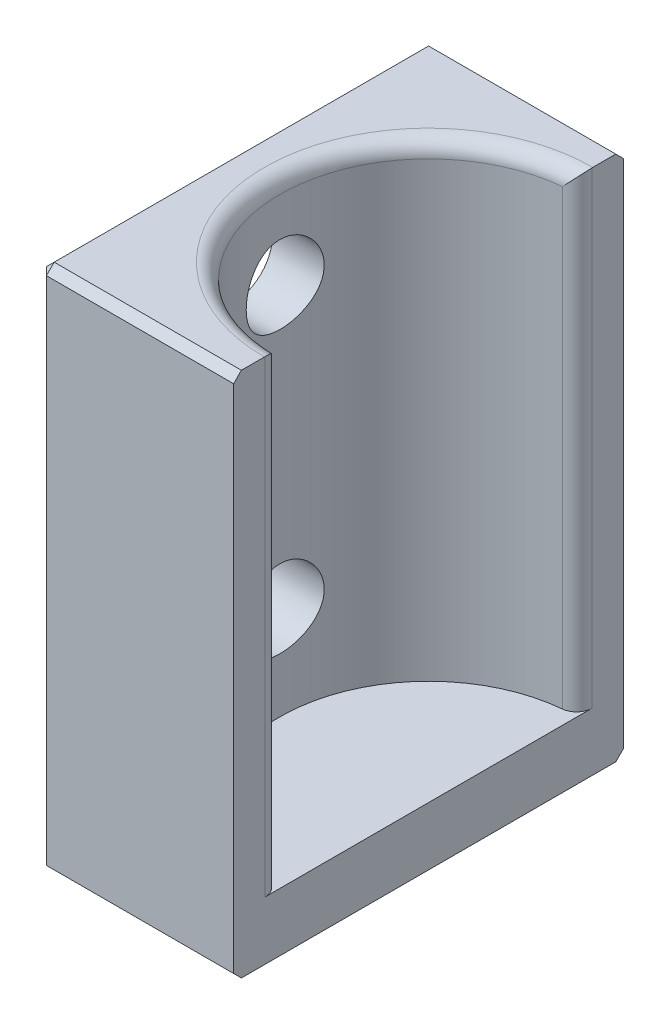
SolidWorks part; units mm, degrees
ref_plane "Front" through (0, 0, 0) normal (0, 0, 1) x (1, 0, 0)
ref_plane "Top" through (0, 0, 0) normal (0, 1, 0) x (1, 0, 0)
ref_plane "Right" through (0, 0, 0) normal (1, 0, 0) x (0, 0, -1)
sketch "Sketch1" plane through (0, 0, 0) normal (0, 1, 0) x (1, 0, 0)
  line L1 (-12.5, -12.5) -> (12.5, -12.5)
  line L2 (-12.5, -12.5) -> (-12.5, 12.5)
  line L3 (-12.5, 12.5) -> (12.5, 12.5)
  line L4 (12.5, -12.5) -> (12.5, 12.5)
  line L5 (-12.5, -12.5) -> (12.5, 12.5) construction
  line L6 (-12.5, 12.5) -> (12.5, -12.5) construction
  point P0 (0, 0)
  dimension "D1" = 25
extrude "Boss-Extrude1" add sketch "Sketch1" along normal blind 33.74
sketch "Sketch2" plane through (0, 33.74, 0) normal (0, 1, 0) x (1, 0, 0)
  line L0 (-12.5, 12.5) -> (12.5, -12.5) construction
  circle A0 centre (0, 0) radius 9.525
  dimension "D1" = 19.05
extrude "Cut-Extrude1" cut sketch "Sketch2" against normal blind 30
sketch "Sketch3" plane through (0, 33.74, 0) normal (0, 1, 0) x (1, 0, 0)
  line L0 (0, 12.5) -> (0, -12.5)
  line L1 (12.5, 12.5) -> (-12.5, 12.5) construction
  line L2 (-12.5, -12.5) -> (12.5, -12.5) construction
  line L3 (0, -12.5) -> (12.5, -12.5)
  line L4 (12.5, -12.5) -> (12.5, 12.5)
  line L5 (12.5, 12.5) -> (0, 12.5)
extrude "Cut-Extrude2" cut sketch "Sketch3" against normal through all
sketch "Sketch4" plane through (-12.5, 0, 0) normal (-1, 0, 0) x (0, 0, 1)
  line L0 (0, 33.74) -> (0, 3.74) construction
  line L1 (-12.5, 33.74) -> (12.5, 33.74) construction
  line L2 (-12.5, 18.74) -> (12.5, 18.74) construction
  line L3 (-12.5, 33.74) -> (-12.5, 0) construction
  line L4 (12.5, 33.74) -> (12.5, 0) construction
  circle A0 centre (0, 27.74) radius 2.5
  circle A1 centre (0, 9.74) radius 2.5
  point P11 (0, 18.74)
  dimension "D2" = 5
  dimension "D1" = 30
  dimension "D3" = 6
extrude "Cut-Extrude3" cut sketch "Sketch4" against normal through all
chamfer "Chamfer2" distance 0.5 angle 45 8 edges at (-12.5, 16.87, -12.5) (-12.5, 33.74, 0) (-12.5, 16.87, 12.5) (-12.5, 0, 0) (-6.25, 33.74, -12.5) (-6.25, 0, -12.5) (-6.25, 0, 12.5) (-6.25, 33.74, 12.5)
fillet "Fillet1" radius 1 3 edges at (-9.525, 33.74, 0) (0, 18.74, 9.525) (0, 18.74, -9.525)
